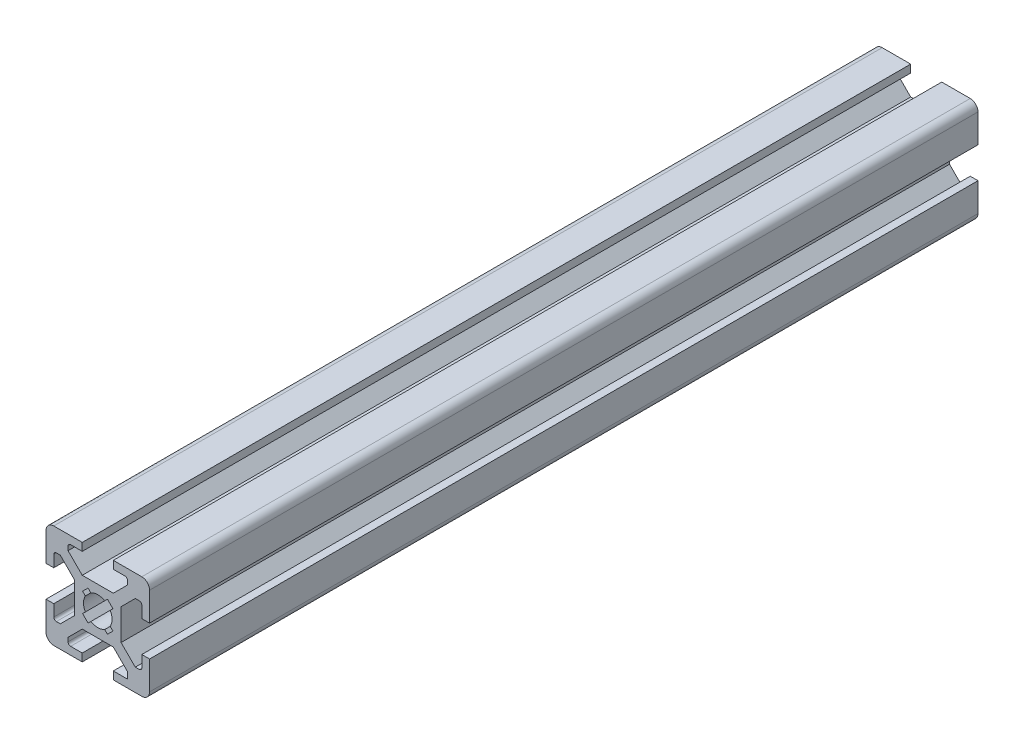
SolidWorks part; units mm, degrees
ref_plane "Alzado" through (0, 0, 0) normal (0, 0, 1) x (1, 0, 0)
ref_plane "Planta" through (0, 0, 0) normal (0, 1, 0) x (1, 0, 0)
ref_plane "Vista lateral" through (0, 0, 0) normal (1, 0, 0) x (0, 0, -1)
other "Tabla de configuración"
sketch "Croquis1" plane through (0, 0, 0) normal (0, 0, 1) x (1, 0, 0)
  line L0 (3, -4.5) -> (5.7414, -7.2414)
  line L1 (-10, 10) -> (-3, 10)
  line L2 (-10, 10) -> (-10, 3)
  line L3 (-10, -10) -> (-3, -10)
  line L4 (10, 10) -> (10, 3)
  line L5 (-10, 10) -> (10, -10) construction
  line L6 (-10, -10) -> (10, 10) construction
  line L7 (-3, 4.5) -> (3, 4.5)
  line L8 (-4.5, 3) -> (-4.5, -3)
  line L9 (-3, -4.5) -> (3, -4.5)
  line L10 (4.5, 3) -> (4.5, -3)
  line L11 (-4.5, 4.5) -> (4.5, -4.5) construction
  line L12 (-4.5, -4.5) -> (4.5, 4.5) construction
  line L13 (5.7414, -7.2414) -> (5.7414, -8.5)
  line L14 (5.7414, -8.5) -> (3, -8.5)
  line L15 (3, -8.5) -> (3, -10)
  line L16 (-7.2414, 5.7414) -> (-4.5, 3)
  line L17 (-3, -10) -> (-3, -8.5)
  line L18 (-3, -8.5) -> (-5.7414, -8.5)
  line L19 (-5.7414, -8.5) -> (-5.7414, -7.2414)
  line L20 (-5.7414, -7.2414) -> (-3, -4.5)
  line L21 (0, -4.5) -> (0, -10) construction
  line L22 (3, -10) -> (10, -10)
  line L24 (-4.5, -3) -> (-7.2414, -5.7414)
  line L25 (-7.2414, -5.7414) -> (-8.5, -5.7414)
  line L26 (-8.5, -5.7414) -> (-8.5, -3)
  line L27 (-8.5, -3) -> (-10, -3)
  line L28 (-10, 3) -> (-8.5, 3)
  line L29 (-8.5, 3) -> (-8.5, 5.7414)
  line L30 (-8.5, 5.7414) -> (-7.2414, 5.7414)
  line L31 (5.7414, 7.2414) -> (3, 4.5)
  line L33 (-3, 4.5) -> (-5.7414, 7.2414)
  line L34 (-5.7414, 7.2414) -> (-5.7414, 8.5)
  line L35 (-5.7414, 8.5) -> (-3, 8.5)
  line L36 (-3, 8.5) -> (-3, 10)
  line L37 (3, 10) -> (3, 8.5)
  line L38 (3, 8.5) -> (5.7414, 8.5)
  line L39 (5.7414, 8.5) -> (5.7414, 7.2414)
  line L40 (7.2414, -5.7414) -> (4.5, -3)
  line L42 (4.5, 3) -> (7.2414, 5.7414)
  line L43 (7.2414, 5.7414) -> (8.5, 5.7414)
  line L44 (8.5, 5.7414) -> (8.5, 3)
  line L45 (8.5, 3) -> (10, 3)
  line L46 (10, -3) -> (8.5, -3)
  line L47 (8.5, -3) -> (8.5, -5.7414)
  line L48 (8.5, -5.7414) -> (7.2414, -5.7414)
  line L49 (3, 10) -> (10, 10)
  line L50 (-10, -3) -> (-10, -10)
  line L51 (10, -3) -> (10, -10)
  line L52 (3, 4.5) -> (-3, 4.5) [skipped]
  line L53 (-4.5, 3) -> (-4.5, -3) [skipped]
  line L54 (4.5, -3) -> (4.5, 3) [skipped]
  point P0 (0, 0)
  point P6 (0, 0)
  point P26 (0, 0)
  point P37 (0, 0)
  point P48 (0, 0)
  point P59 (0, 0)
  dimension "D1" = 20
  dimension "D2" = 1.5
  dimension "D3" = 9
  dimension "D4" = 7
  dimension "D5" = 6
  dimension "D6" = 4
  dimension "D7" = 5.5
extrude "Saliente-Extruir1" add sketch "Croquis1" along normal blind 160
fillet "Redondeo1" radius 1.5 4 edges at (10, -10, 80) (-10, -10, 80) (10, 10, 80) (-10, 10, 80)
fillet "Redondeo2" radius 0.5 7 edges at (-5.7414, -8.5, 80) (5.7414, 8.5, 80) (-5.7414, 8.5, 80) (8.5, -5.7414, 80) (-8.5, -5.7414, 80) (8.5, 5.7414, 80) (-8.5, 5.7414, 80)
sketch "Croquis2" plane through (0, 0, 0) normal (0, 0, -1) x (-1, 0, 0)
  line L0 (-1.3405, 2.4012) -> (-1.8708, 2.9315)
  line L1 (-1.8708, 2.9315) -> (-2.9315, 1.8708)
  line L2 (-2.9315, 1.8708) -> (-2.4012, 1.3405)
  line L3 (-4.5, 3) -> (-7.2414, 5.7414) construction
  line L5 (1.8708, 2.9315) -> (1.3405, 2.4012)
  line L6 (2.9315, 1.8708) -> (1.8708, 2.9315)
  line L7 (2.4012, 1.3405) -> (2.9315, 1.8708)
  line L8 (2.9315, -1.8708) -> (2.4012, -1.3405)
  line L9 (1.8708, -2.9315) -> (2.9315, -1.8708)
  line L10 (1.3405, -2.4012) -> (1.8708, -2.9315)
  line L11 (-1.8708, -2.9315) -> (-1.3405, -2.4012)
  line L12 (-2.9315, -1.8708) -> (-1.8708, -2.9315)
  line L13 (-2.4012, -1.3405) -> (-2.9315, -1.8708)
  arc A0 (-2.4012, 1.3405) -> (-2.4012, -1.3405) centre (0, 0) ccw
  arc A1 (-1.3405, -2.4012) -> (1.3405, -2.4012) centre (0, 0) ccw
  arc A2 (2.4012, -1.3405) -> (2.4012, 1.3405) centre (0, 0) ccw
  arc A3 (1.3405, 2.4012) -> (-1.3405, 2.4012) centre (0, 0) ccw
  point P25 (0, 0)
  dimension "D1" = 5.5
  dimension "D2" = 0.75
  dimension "D3" = 1.5
  dimension "D4" = 4
extrude "Cortar-Extruir1" cut sketch "Croquis2" against normal through all
